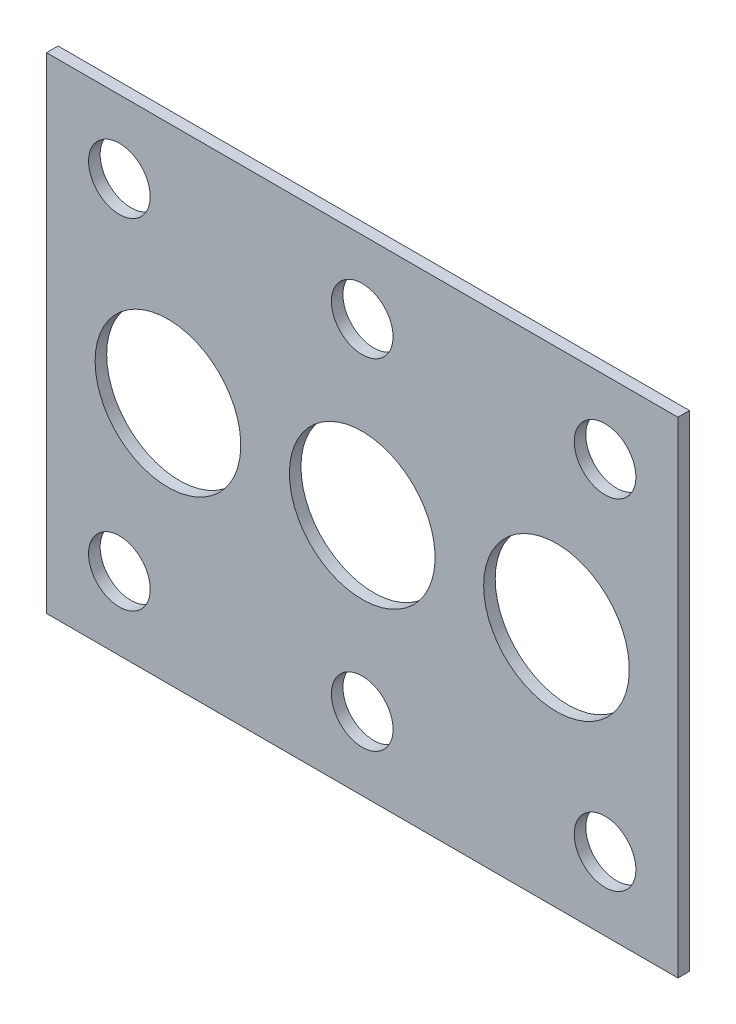
SolidWorks part; units mm, degrees
material "AISI 1020"
ref_plane "Plano frontal" through (0, 0, 0) normal (0, 0, 1) x (1, 0, 0)
ref_plane "Plano superior" through (0, 0, 0) normal (0, 1, 0) x (1, 0, 0)
ref_plane "Plano direito" through (0, 0, 0) normal (1, 0, 0) x (0, 0, -1)
sketch "Esboço1" plane through (0, 0, 0) normal (0, 0, 1) x (1, 0, 0)
  line L0 (-100, 140) -> (-100, 0) construction
  line L1 (0, 0) -> (-200, 0) construction
  line L2 (0, 0) -> (0, 140) construction
  line L3 (0, 140) -> (-200, 140) construction
  line L4 (-200, 0) -> (-200, 140) construction
  line L6 (-230, 170) -> (30, 170)
  line L7 (-230, 170) -> (-230, -30)
  line L8 (-230, -30) -> (30, -30)
  line L9 (30, 170) -> (30, -30)
  line L10 (-230, 170) -> (30, -30) construction
  line L11 (-230, -30) -> (30, 170) construction
  circle A0 centre (0, 0) radius 12.7
  circle A1 centre (-100, 0) radius 12.7
  circle A2 centre (-200, 0) radius 12.7
  circle A3 centre (-200, 140) radius 12.7
  circle A4 centre (-100, 140) radius 12.7
  circle A5 centre (0, 140) radius 12.7
  circle A6 centre (-100, 70) radius 30
  circle A7 centre (-20, 70) radius 30
  circle A8 centre (-180, 70) radius 30
  point P14 (-100, 70)
  point P25 (0, 0)
  dimension "D3" = 25.4
  dimension "D6" = 60
  dimension "D1" = 140
  dimension "D2" = 200
  dimension "D4" = 200
  dimension "D5" = 260
  dimension "D7" = 2
extrude "Ressalto-extrusão1" add sketch "Esboço1" along normal blind 4.7625
